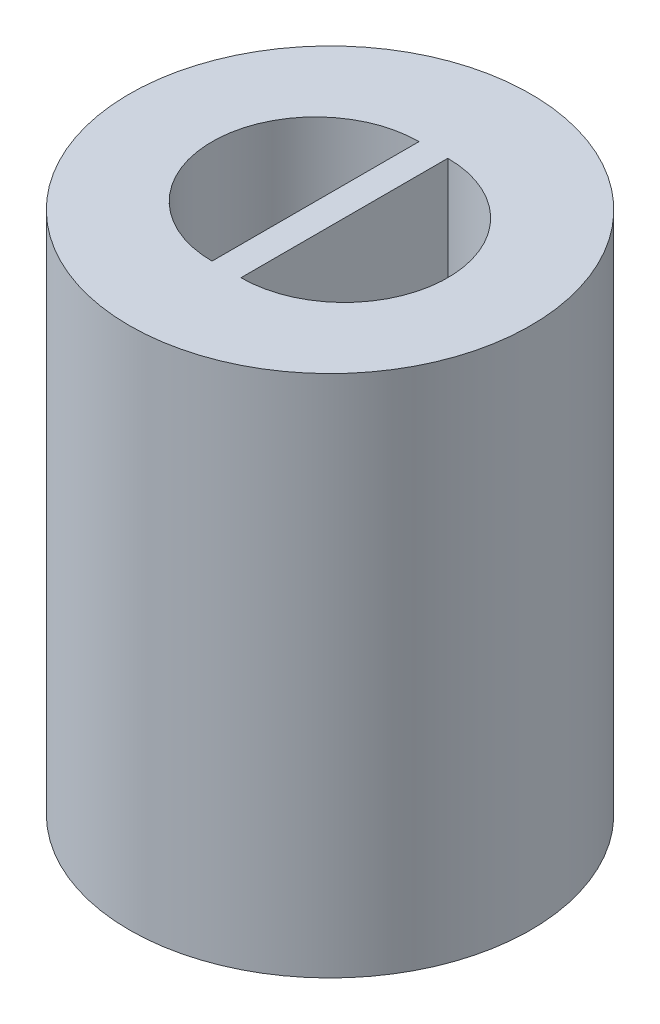
SolidWorks part; units mm, degrees
ref_plane "Front Plane" through (0, 0, 0) normal (0, 0, 1) x (1, 0, 0)
ref_plane "Top Plane" through (0, 0, 0) normal (0, 1, 0) x (1, 0, 0)
ref_plane "Right Plane" through (0, 0, 0) normal (1, 0, 0) x (0, 0, -1)
sketch "Sketch1" plane through (0, 0, 0) normal (0, 1, 0) x (1, 0, 0)
  circle A0 centre (0, 0) radius 5.75
  dimension "D1" = 11.5
extrude "Boss-Extrude1" add sketch "Sketch1" along normal blind 15
sketch "Sketch6" plane through (0, 15, 0) normal (0, 1, 0) x (1, 0, 0)
  line L4 (0.41, 2.9647) -> (0.41, -2.9647)
  line L5 (-0.4164, 2.9656) -> (-0.4164, -2.9656)
  arc A3 (0.41, 2.9647) -> (0.41, -2.9647) centre (0.41, 0) cw
  arc A4 (-0.4164, 2.9656) -> (-0.4164, -2.9656) centre (-0.4164, 0) ccw
  dimension "D2" = 0.41
extrude "Cut-Extrude3" cut sketch "Sketch6" against normal blind 8
sketch "Sketch7" plane through (0, 0, 0) normal (0, 1, 0) x (1, 0, 0)
  line L1 (-1.85, 2.75) -> (1.85, 2.75)
  line L2 (-1.85, 2.75) -> (-1.85, -2.75)
  line L3 (-1.85, -2.75) -> (1.85, -2.75)
  line L4 (1.85, 2.75) -> (1.85, -2.75)
  line L5 (-1.85, 2.75) -> (1.85, -2.75) construction
  line L6 (-1.85, -2.75) -> (1.85, 2.75) construction
  point P0 (0, 0)
  dimension "D1" = 5.5
  dimension "D2" = 3.7
extrude "Cut-Extrude4" cut sketch "Sketch7" along normal blind 6.5
